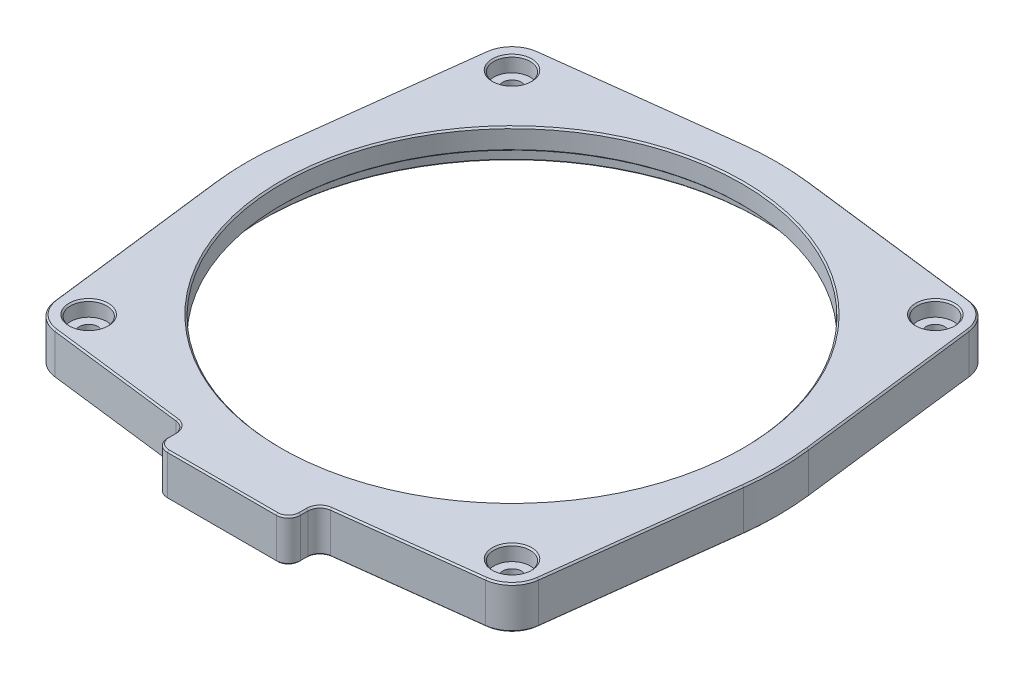
SolidWorks part; units mm, degrees
ref_plane "Płaszczyzna przednia" through (0, 0, 0) normal (0, 0, 1) x (1, 0, 0)
ref_plane "Płaszczyzna górna" through (0, 0, 0) normal (0, 1, 0) x (1, 0, 0)
ref_plane "Płaszczyzna prawa" through (0, 0, 0) normal (1, 0, 0) x (0, 0, -1)
sketch "Szkic1" plane through (0, 0, 0) normal (0, 0, 1) x (1, 0, 0)
  line L0 (0, 0) -> (0, 24.6386) construction
  line L1 (0, 0) -> (-44, 0) construction
  line L2 (-44, 0) -> (-44, 7)
  line L3 (-44, 7) -> (-38, 7)
  line L4 (-38, 7) -> (-38, 3.5)
  line L5 (-38, 3.5) -> (-41, 3.5)
  line L6 (-41, 3.5) -> (-41, 0)
  line L7 (-41, 0) -> (-44, 0)
  dimension "D1" = 44
  dimension "D2" = 3
  dimension "D3" = 6
  dimension "D4" = 3.5
  dimension "D5" = 7
revolve "Obrót1" add sketch "Szkic1" angle 360 about L0
sketch "Szkic2" plane through (0, 7, 0) normal (0, 1, 0) x (1, 0, 0)
  line L0 (0, 0) -> (-35, 35) construction
  line L1 (-3.5355, -3.5355) -> (-38.5355, 31.4645)
  line L2 (3.5355, 3.5355) -> (-31.4645, 38.5355)
  line L3 (0, 0) -> (0, 56.3355) construction
  arc A0 (-3.5355, -3.5355) -> (3.5355, 3.5355) centre (0, 0) ccw
  arc A1 (-31.4645, 38.5355) -> (-38.5355, 31.4645) centre (-35, 35) ccw
  arc A2 (-27.3756, 34.4467) -> (-34.4467, 27.3756) centre (0, 0) ccw
  circle A3 centre (0, 0) radius 44 construction
  circle A4 centre (-35, 35) radius 1.55
  point P3 (-17.5, 17.5)
  circle M7 centre (0, 0) radius 44
  dimension "D4" = 3.1
  dimension "D1" = 45
  dimension "D2" = 10
  dimension "D3" = 35
extrude "Dodanie-wyciągnięcie1" add sketch "Szkic2" against normal up to surface (7 mm away) contours L2 A1 L1 A4 M7 up to face at (0, 0, -41)
sketch "Szkic3" plane through (0, 7, 0) normal (0, 1, 0) x (1, 0, 0)
  circle A0 centre (-35, 35) radius 3
  dimension "D1" = 6
extrude "Wytnij-wyciągnięcie1" cut sketch "Szkic3" against normal blind 2.5
pattern_circular "Szyk kołowy3" count 4 over 360 about axis through (0, 0, 0) along (0, 1, 0) of "Dodanie-wyciągnięcie1", "Wytnij-wyciągnięcie1"
sketch "Szkic4" plane through (0, 7, 0) normal (0, 1, 0) x (1, 0, 0)
  line L0 (-43.6728, 5.3557) -> (-39.9628, 35.6086)
  line L1 (-34.4467, 27.3756) -> (-38.5355, 31.4645) construction
  line L2 (-34.4467, 27.3756) -> (-38.5355, 31.4645)
  arc A0 (-34.4467, 27.3756) -> (-34.4467, -27.3756) centre (0, 0) ccw construction
  arc A1 (-31.4645, 38.5355) -> (-38.5355, 31.4645) centre (-35, 35) ccw construction
  arc A2 (-31.4645, 38.5355) -> (-38.5355, 31.4645) centre (-35, 35) ccw
  arc A3 (-34.4467, 27.3756) -> (-34.4467, -27.3756) centre (0, 0) ccw
  arc M8 (-31.4645, 38.5355) -> (-38.5355, 31.4645) centre (-35, 35) ccw
  line M9 (-38.5355, 31.4645) -> (-34.4467, 27.3756)
  arc M10 (-34.4467, 27.3756) -> (-34.4467, -27.3756) centre (0, 0) ccw
extrude "Dodanie-wyciągnięcie2" add sketch "Szkic4" against normal up to surface (7 mm away) contours L0 M10 M9 M8
mirror "Lustro1" about plane through (0, 0, 0) normal (0, 0, 1) of "Dodanie-wyciągnięcie2" second plane through (0, 0, 0) second plane normal (1, 0, 0)
pattern_circular "Szyk kołowy4" count 4 over 360 about axis through (0, 0, 0) along (0, -1, 0) of "Lustro1"
sketch "Szkic6" plane through (0, 7, 0) normal (0, 1, 0) x (1, 0, 0)
  line L0 (-11, -42.9807) -> (11, -42.9807)
  line L1 (-11, -42.9807) -> (-11, -47.9807)
  line L2 (11, -42.9807) -> (11, -47.9807)
  line L3 (-11, -47.9807) -> (11, -47.9807)
  line L4 (-5.3557, -43.6728) -> (-35.6086, -39.9628) construction
  line L5 (5.3557, -43.6728) -> (35.6086, -39.9628) construction
  dimension "D1" = 22
  dimension "D2" = 5
extrude "Dodanie-wyciągnięcie3" add sketch "Szkic6" against normal up to surface (7 mm away)
fillet "Zaokrąglenie1" radius 2 4 edges at (-11, 3.5, 47.9807) (-11, 3.5, 42.9807) (11, 3.5, 42.9807) (11, 3.5, 47.9807)
chamfer "Sfazowanie1" distance 0.25 angle 45 55 edges at (-38.5355, 0, -38.5355) (-41.8178, 0, -20.4822) (-41.8178, 7, -20.4822) (38.5355, 7, -38.5355) (44, 7, 0) (44, 0, 0) (41.8178, 7, -20.4822) (41.8178, 0, -20.4822) (-38.5355, 7, 38.5355) (-44, 7, 0) (-44, 0, 0) (-41.8178, 7, 20.4822) (-41.8178, 0, 20.4822) (38.5355, 0, 38.5355) (41.8178, 0, 20.4822) (41.8178, 7, 20.4822) (-38.5355, 7, -38.5355) (0, 7, -44) (0, 0, -44) (-20.4822, 7, -41.8178) (-20.4822, 0, -41.8178) (38.5355, 7, 38.5355) (24.1826, 0, 41.364) (38.5355, 0, -38.5355) (-35, 0, -33.45) (20.4822, 0, -41.8178) (20.4822, 7, -41.8178) (-38.5355, 0, 38.5355) (-24.1826, 0, 41.364) (-35, 7, -32) (11, 0, 45.3655) (11, 7, 45.3655) (24.1826, 7, 41.364) (0, 0, 47.9807) (0, 7, 47.9807) (-24.1826, 7, 41.364) (-11, 7, 45.3655) (-10.4142, 7, 47.3949) (10.4142, 7, 47.3949) (-11, 0, 45.3655) (-10.4142, 0, 47.3949) (10.4142, 0, 47.3949) (11.5022, 7, 43.425) (11.5022, 0, 43.425) (-11.5022, 7, 43.425) (-11.5022, 0, 43.425) (35, 0, -33.45) (35, 0, 36.55) (0, 0, -41) (0, 3.5, -38) (0, 7, -38) (-35, 0, 36.55) (32, 7, -35) (35, 7, 32) (-32, 7, 35)
sketch "Szkic7" plane through (0, 0, 0) normal (0, -1, 0) x (1, 0, 0)
  line L0 (0, 42.4805) -> (-1.5, 46.4805)
  line L1 (-1.5, 46.4805) -> (1.5, 46.4805)
  line L2 (1.5, 46.4805) -> (0, 42.4805)
  line L3 (0, 42.4805) -> (0, 0) construction
  dimension "D1" = 4
  dimension "D2" = 3
extrude "Wytnij-wyciągnięcie2" cut sketch "Szkic7" against normal blind 1
